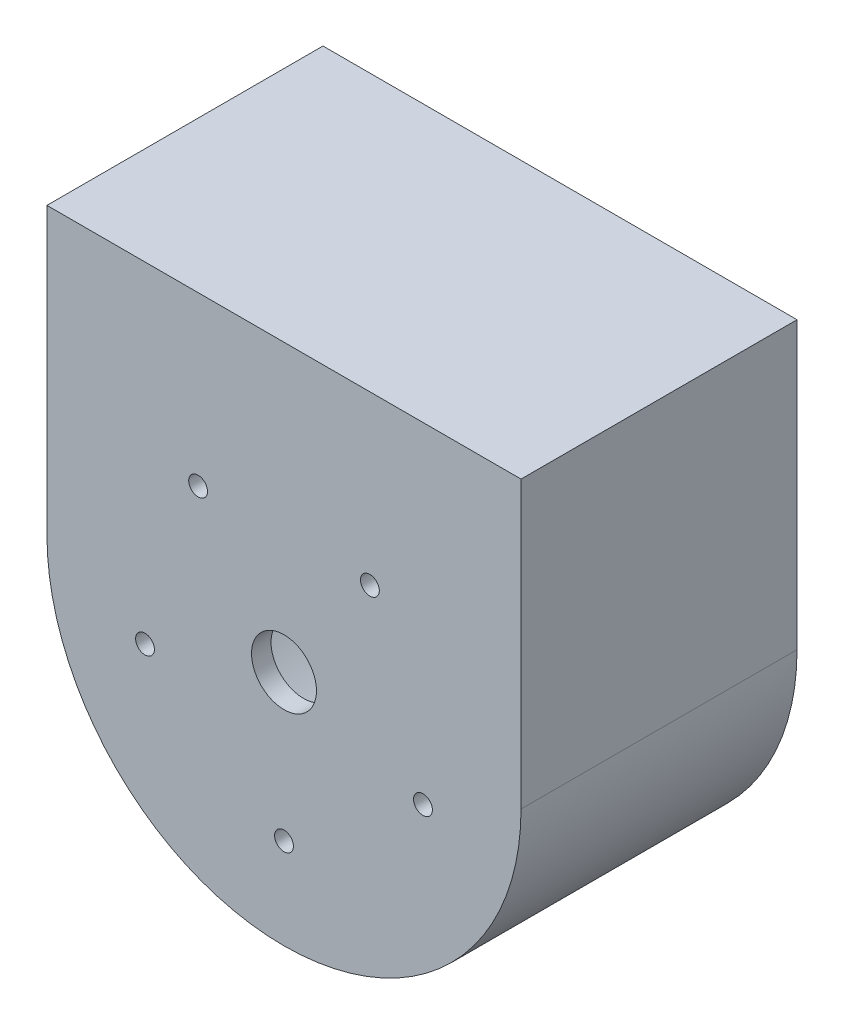
SolidWorks part; units mm, degrees
ref_plane "Front Plane" through (0, 0, 0) normal (0, 0, 1) x (1, 0, 0)
ref_plane "Top Plane" through (0, 0, 0) normal (0, 1, 0) x (1, 0, 0)
ref_plane "Right Plane" through (0, 0, 0) normal (1, 0, 0) x (0, 0, -1)
ref_plane "Plane1" through (0, 0, 350) normal (0, 0, 1) x (1, 0, 0)
sketch "Sketch1" plane through (0, 0, 350) normal (0, 0, 1) x (1, 0, 0)
  circle A0 centre (300, 300) radius 36.5
extrude "Boss-Extrude1" add sketch "Sketch1" along normal blind 42.5
sketch "Sketch2" plane through (0, 0, 350) normal (0, 0, 1) x (1, 0, 0)
  line L0 (263.5, 300) -> (336.5, 300)
  line L1 (336.5, 300) -> (336.5, 344)
  line L2 (336.5, 344) -> (263.5, 344)
  line L3 (263.5, 344) -> (263.5, 300)
extrude "Boss-Extrude2" add sketch "Sketch2" along normal blind 42.5
sketch "Sketch3" plane through (0, 0, 350) normal (0, 0, 1) x (1, 0, 0)
  circle A0 centre (300, 300) radius 31.5
extrude "Cut-Extrude1" cut sketch "Sketch3" along normal blind 39.5
sketch "Sketch4" plane through (0, 0, 350) normal (0, 0, 1) x (1, 0, 0)
  line L0 (268.5, 300) -> (331.5, 300)
  line L1 (331.5, 300) -> (331.5, 341.5)
  line L2 (331.5, 341.5) -> (268.5, 341.5)
  line L3 (268.5, 341.5) -> (268.5, 300)
extrude "Cut-Extrude2" cut sketch "Sketch4" along normal blind 39.5
ref_plane "Plane2" through (0, 0, 389.5) normal (0, 0, 1) x (1, 0, 0)
sketch "Sketch5" plane through (0, 0, 389.5) normal (0, 0, 1) x (1, 0, 0)
  circle A0 centre (300, 300) radius 5
  circle A1 centre (286.7748, 318.2029) radius 1.45
  circle A2 centre (278.6012, 293.0471) radius 1.45
  circle A3 centre (300, 277.5) radius 1.45
  circle A4 centre (321.3988, 293.0471) radius 1.45
  circle A5 centre (313.2252, 318.2029) radius 1.45
extrude "Cut-Extrude3" cut sketch "Sketch5" along normal blind 3
